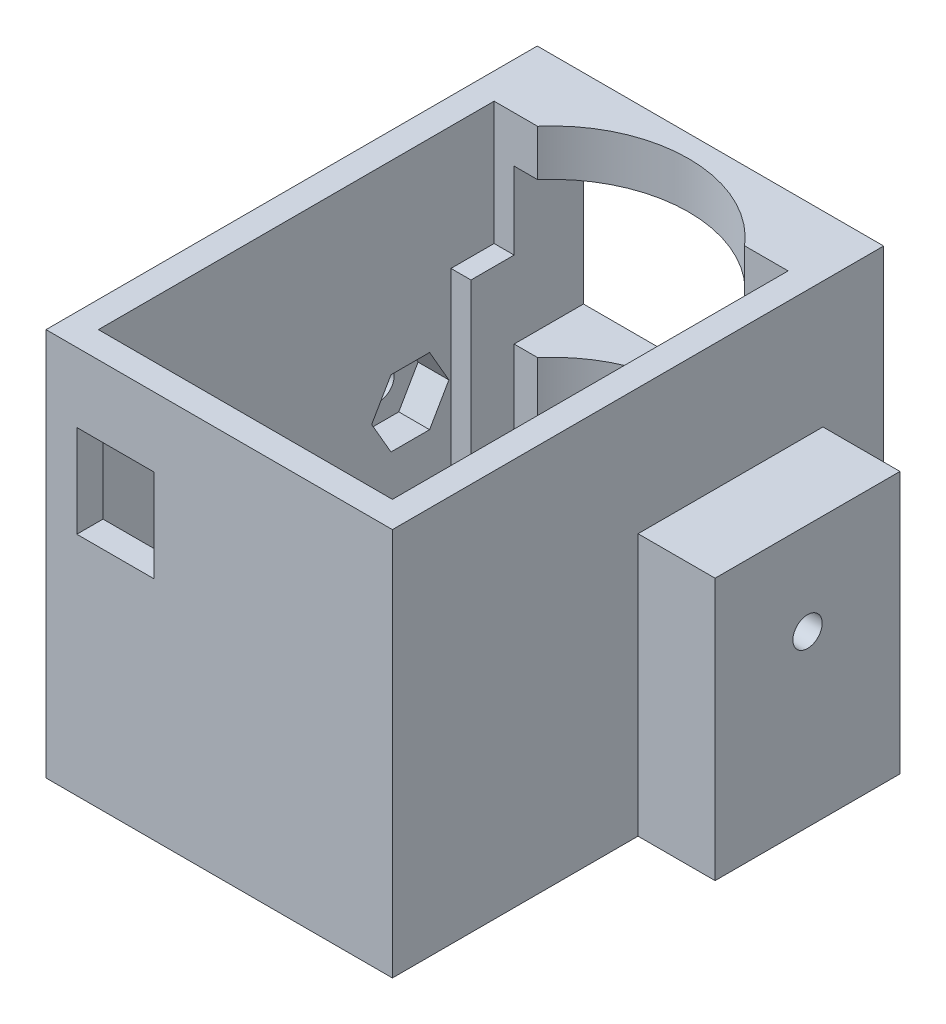
SolidWorks part; units mm, degrees
ref_plane "Front Plane" through (0, 0, 0) normal (0, 0, 1) x (1, 0, 0)
ref_plane "Top Plane" through (0, 0, 0) normal (0, 1, 0) x (1, 0, 0)
ref_plane "Right Plane" through (0, 0, 0) normal (1, 0, 0) x (0, 0, -1)
sketch "Sketch1" plane through (0, 0, 0) normal (0, 1, 0) x (1, 0, 0)
  line L0 (8.6832, 19.7079) -> (8.6832, 13.9379)
  line L1 (-0.8568, -5.9721) -> (18.2232, -5.9721)
  line L2 (-0.8568, -5.9721) -> (-0.8568, 19.7079)
  line L3 (-0.8568, 19.7079) -> (18.2232, 19.7079)
  line L4 (18.2232, -5.9721) -> (18.2232, 19.7079)
  line L5 (-0.8568, -5.9721) -> (-0.8568, -7.6721)
  line L6 (-0.8568, -7.6721) -> (-2.5568, -7.6721)
  line L7 (18.2232, 19.7079) -> (18.2232, 24.2079)
  line L8 (18.2232, 24.2079) -> (19.9232, 24.2079)
  line L10 (-2.5568, -7.6721) -> (19.9232, -7.6721)
  line L11 (-2.5568, -7.6721) -> (-2.5568, 24.2079)
  line L12 (-2.5568, 24.2079) -> (19.9232, 24.2079)
  line L13 (19.9232, -7.6721) -> (19.9232, 24.2079)
  circle A0 centre (8.6832, 13.9379) radius 8.855
  dimension "D4" = 17.71
  dimension "D1" = 25.68
  dimension "D2" = 19.08
  dimension "D3" = 5.77
  dimension "D5" = 4.5
  dimension "D6" = 1.7
  dimension "D7" = 1.7
  dimension "D8" = 1.7
extrude "Boss-Extrude1" add sketch "Sketch1" along normal blind 23.2 contours L10 L13 L8 L7 L4 L1 L5 | A0 L3 L7 L12 L11 L6 L5 L2
sketch "Sketch2" plane through (0, 0, 0) normal (0, -1, 0) x (1, 0, 0)
  line L0 (-2.5568, 7.6721) -> (19.9232, 7.6721) construction
  line L1 (8.6832, 7.6721) -> (13.6832, 7.6721)
  line L2 (8.6832, 7.6721) -> (8.6832, -24.2079)
  line L3 (8.6832, -24.2079) -> (13.6832, -24.2079)
  line L4 (13.6832, 7.6721) -> (13.6832, -24.2079)
  line L5 (-2.5568, -24.2079) -> (19.9232, -24.2079) construction
  line L7 (8.6832, 7.6721) -> (3.6832, 7.6721)
  line L8 (8.6832, 7.6721) -> (8.6832, -24.2079)
  line L9 (8.6832, -24.2079) -> (3.6832, -24.2079)
  line L10 (3.6832, 7.6721) -> (3.6832, -24.2079)
  line L11 (-2.5568, 7.6721) -> (19.9232, 7.6721)
  line L12 (-2.5568, 7.6721) -> (-2.5568, -24.2079)
  line L13 (-2.5568, -24.2079) -> (19.9232, -24.2079)
  line L14 (19.9232, 7.6721) -> (19.9232, -24.2079)
  line M3 (-2.5568, -24.2079) -> (19.9232, -24.2079)
  line M4 (19.9232, -24.2079) -> (19.9232, 7.6721)
  line M5 (19.9232, 7.6721) -> (-2.5568, 7.6721)
  line M6 (-2.5568, 7.6721) -> (-2.5568, -24.2079)
  line M7 (18.2232, -19.7079) -> (15.4002, -19.7079)
  arc M8 (15.4002, -19.7079) -> (1.9662, -19.7079) centre (8.6832, -13.9379) cw
  line M9 (1.9662, -19.7079) -> (-0.8568, -19.7079)
  line M10 (-0.8568, -19.7079) -> (-0.8568, 5.9721)
  line M11 (-0.8568, 5.9721) -> (18.2232, 5.9721)
  line M12 (18.2232, 5.9721) -> (18.2232, -19.7079)
  dimension "D1" = 5
  dimension "D2" = 5
extrude "Boss-Extrude2" add sketch "Sketch2" along normal blind 2 contours L10 M5 M6 M3 M8 M9 M10 M11 | L10 L2 M8 M3 | L4 L2 M8 M3 | L4 M5 M11 M12 M7 M8 M3 M4 | L4 L2 M5 M11 | L10 L2 M5 M11 | L4 L2 M11 M8 | L10 L2 M11 M8
sketch "Sketch3" plane through (0, 0, 7.6721) normal (0, 0, 1) x (1, 0, 0)
  line L1 (-2.5568, 23.2) -> (4.4432, 23.2)
  line L2 (-2.5568, 23.2) -> (-2.5568, 12.7)
  line L3 (-2.5568, 12.7) -> (4.4432, 12.7)
  line L4 (4.4432, 23.2) -> (4.4432, 12.7)
  line L5 (4.4432, 12.7) -> (-0.5568, 12.7)
  line L6 (4.4432, 12.7) -> (4.4432, 18.7)
  line L7 (4.4432, 18.7) -> (-0.5568, 18.7)
  line L8 (-0.5568, 12.7) -> (-0.5568, 18.7)
  dimension "D1" = 6
  dimension "D2" = 5
  dimension "D3" = 7
  dimension "D4" = 10.5
extrude "Cut-Extrude1" cut sketch "Sketch3" against normal blind 2 contours L8 L3 L4 L7
sketch "Sketch4" plane through (0, 0, -24.2079) normal (0, 0, -1) x (-1, 0, 0)
  line L0 (-19.9232, 23.2) -> (-16.9232, 23.2)
  line L1 (2.5568, 23.2) -> (-19.9232, 23.2) construction
  line L2 (-16.9232, 23.2) -> (-16.9232, 20.2)
  line L3 (2.5568, 23.2) -> (-0.4432, 23.2)
  line L4 (-0.4432, 23.2) -> (-0.4432, 20.2)
  line L6 (-16.9232, 20.2) -> (-0.4432, 20.2)
  line L7 (-16.9232, 20.2) -> (-16.9232, 10.2)
  line L8 (-16.9232, 10.2) -> (-0.4432, 10.2)
  line L9 (-0.4432, 20.2) -> (-0.4432, 10.2)
  dimension "D1" = 3
  dimension "D2" = 10
extrude "Cut-Extrude2" cut sketch "Sketch4" against normal blind 7 contours L9 L6 L7 L8
sketch "Sketch6" plane through (18.2232, 0, 0) normal (-1, 0, 0) x (0, 0, 1)
  line L0 (-19.7079, 23.2) -> (-19.7079, 15.2)
  line L1 (-19.7079, 23.2) -> (-19.7079, -2) construction
  line L2 (5.9721, -2) -> (-19.7079, -2) construction
  line L3 (-19.7079, 15.2) -> (-16.9079, 15.2)
  line L4 (-19.7079, 15.2) -> (-19.7079, -2)
  line L5 (-19.7079, -2) -> (-16.9079, -2)
  line L6 (-16.9079, 15.2) -> (-16.9079, -2)
  line M3 (-19.7079, 23.2) -> (-19.7079, -2)
  line M4 (-19.7079, -2) -> (5.9721, -2)
  dimension "D1" = 8
  dimension "D2" = 2.8
extrude "Boss-Extrude4" add sketch "Sketch6" along normal up to surface (1.3 mm away) contours L6 L3 M3 M4 up to face at (16.9232, 15.2, -21.9579)
sketch "Sketch8" plane through (-0.8568, 0, 0) normal (1, 0, 0) x (0, 0, -1)
  line L0 (19.7079, 23.2) -> (19.7079, 15.2)
  line L1 (19.7079, 23.2) -> (19.7079, -2) construction
  line L2 (19.7079, -2) -> (-5.9721, -2) construction
  line L3 (19.7079, 15.2) -> (16.9079, 15.2)
  line L4 (19.7079, 15.2) -> (19.7079, -2)
  line L5 (19.7079, -2) -> (16.9079, -2)
  line L6 (16.9079, 15.2) -> (16.9079, -2)
  line M2 (-5.9721, -2) -> (19.7079, -2)
  line M3 (19.7079, -2) -> (19.7079, 23.2)
  dimension "D1" = 8
  dimension "D2" = 2.8
extrude "Boss-Extrude5" add sketch "Sketch8" along normal up to surface (1.3 mm away) contours L3 L6 M2 M3 up to face at (0.4432, 15.2, -21.9579)
sketch "Sketch12" plane through (19.9232, 0, 0) normal (1, 0, 0) x (0, 0, -1)
  line L0 (24.2079, -2) -> (-7.6721, -2) construction
  line L1 (8.2679, -2) -> (20.2679, -2)
  line L2 (8.2679, -2) -> (8.2679, 15)
  line L3 (8.2679, 15) -> (20.2679, 15)
  line L4 (20.2679, -2) -> (20.2679, 15)
  line L5 (14.2679, 15) -> (14.2679, 9)
  circle A0 centre (14.2679, 9) radius 0.95
  dimension "D4" = 1.9
  dimension "D1" = 12
  dimension "D2" = 17
  dimension "D3" = 6
extrude "Boss-Extrude6" add sketch "Sketch12" along normal blind 5
sketch "Sketch13" plane through (-2.5568, 0, 0) normal (-1, 0, 0) x (0, 0, 1)
  line L0 (7.6721, -2) -> (-24.2079, -2) construction
  line L1 (-14.2679, 15) -> (-14.2679, 9)
  line L2 (-8.2679, -2) -> (-20.2679, -2)
  line L3 (-8.2679, -2) -> (-8.2679, 15)
  line L4 (-8.2679, 15) -> (-20.2679, 15)
  line L5 (-20.2679, -2) -> (-20.2679, 15)
  circle A0 centre (-14.2679, 9) radius 0.95
  dimension "D3" = 6
  dimension "3.3" = 1.9
  dimension "D1" = 12
  dimension "D2" = 17
extrude "Boss-Extrude7" add sketch "Sketch13" along normal blind 5
sketch "Sketch15" plane through (19.9232, 0, 0) normal (1, 0, 0) x (0, 0, -1)
  line L2 (16.7736, 9) -> (15.5208, 11.17)
  line L3 (15.5208, 11.17) -> (13.0151, 11.17)
  line L4 (13.0151, 11.17) -> (11.7622, 9)
  line L5 (11.7622, 9) -> (13.0151, 6.83)
  line L6 (13.0151, 6.83) -> (15.5208, 6.83)
  line L7 (15.5208, 6.83) -> (16.7736, 9)
  circle A0 centre (14.2679, 9) radius 2.17 construction
  dimension "D1" = 4.34
extrude "Cut-Extrude3" cut sketch "Sketch15" against normal offset from surface (24.78 mm away) 2 from offset 2
